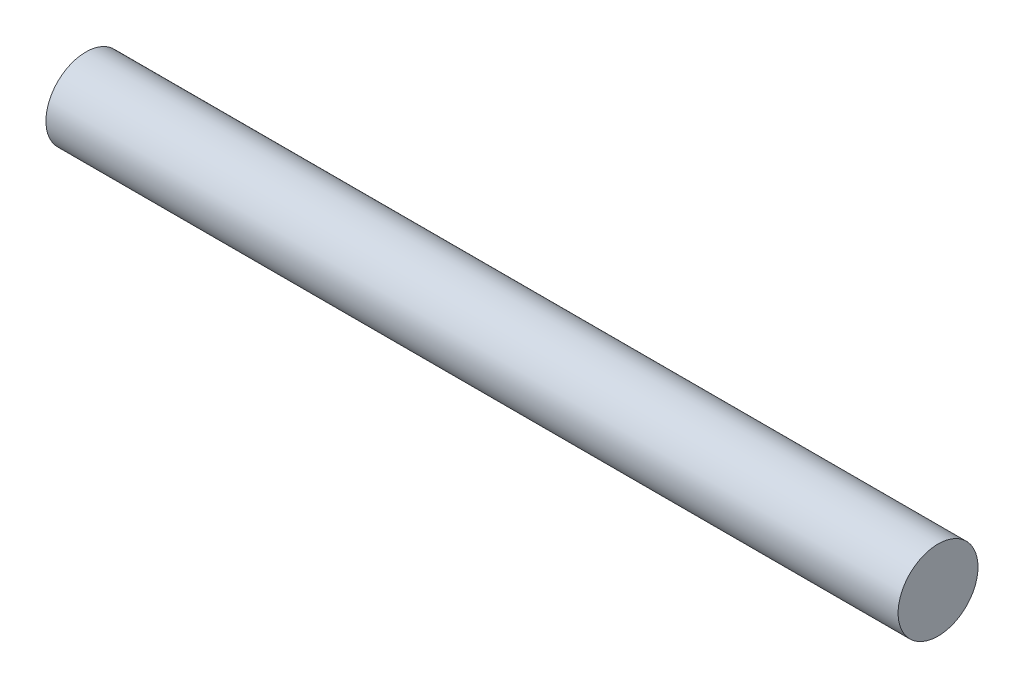
SolidWorks part; units mm, degrees
material "201 Aço inoxidável recozido (SS)"
ref_plane "Plano frontal" through (0, 0, 0) normal (0, 0, 1) x (1, 0, 0)
ref_plane "Plano superior" through (0, 0, 0) normal (0, 1, 0) x (1, 0, 0)
ref_plane "Plano direito" through (0, 0, 0) normal (1, 0, 0) x (0, 0, -1)
sketch "Esboço1" plane through (0, 0, 0) normal (1, 0, 0) x (0, 0, -1)
  circle A0 centre (0, 0) radius 7.5
  dimension "D1" = 15
extrude "Ressalto-extrusão1" add sketch "Esboço1" along normal mid plane 160
